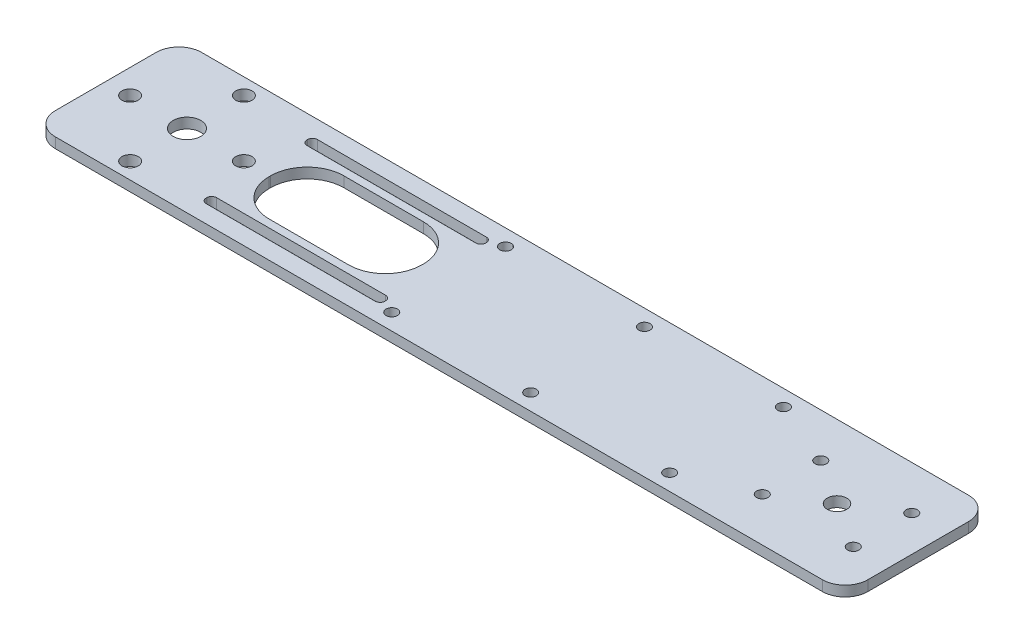
SolidWorks part; units mm, degrees
ref_plane "Front Plane" through (0, 0, 0) normal (0, 0, 1) x (1, 0, 0)
ref_plane "Top Plane" through (0, 0, 0) normal (0, 1, 0) x (1, 0, 0)
ref_plane "Right Plane" through (0, 0, 0) normal (1, 0, 0) x (0, 0, -1)
sketch "Sketch1" plane through (0, 0, 0) normal (0, 1, 0) x (1, 0, 0)
  line L0 (-25, 0) -> (0, 0) construction
  line L1 (-25, 22.5) -> (225, 22.5)
  line L2 (-25, 22.5) -> (-25, -22.5)
  line L3 (-25, -22.5) -> (225, -22.5)
  line L4 (225, 22.5) -> (225, -22.5)
  dimension "D1" = 25
  dimension "D2" = 250
  dimension "D3" = 45
extrude "Boss-Extrude1" add sketch "Sketch1" along normal blind 3.175
sketch "Sketch4" plane through (0, 3.175, 0) normal (0, 1, 0) x (1, 0, 0)
  line L0 (225, 0) -> (-25, 0) construction
  line L1 (225, -22.5) -> (225, 22.5) construction
  line L2 (-25, 22.5) -> (-25, -22.5) construction
  line L3 (200, 22.5) -> (200, -22.5) construction
  line L4 (225, 22.5) -> (-25, 22.5) construction
  line L5 (-25, -22.5) -> (225, -22.5) construction
  circle A0 centre (200, 0) radius 3
  circle A1 centre (186, 9) radius 1.75
  circle A2 centre (214, 9) radius 1.75
  circle A3 centre (214, -9) radius 1.75
  circle A4 centre (186, -9) radius 1.75
  dimension "D1" = 6
  dimension "D5" = 3.5
  dimension "D2" = 25
  dimension "D3" = 14
  dimension "D4" = 9
extrude "Cut-Extrude1" cut sketch "Sketch4" against normal through all
sketch "Sketch5" plane through (0, 3.175, 0) normal (0, 1, 0) x (1, 0, 0)
  circle A0 centre (0, 0) radius 4.25
  dimension "D1" = 8.5
extrude "Cut-Extrude2" cut sketch "Sketch5" against normal through all
sketch "Sketch6" plane through (0, 3.175, 0) normal (0, 1, 0) x (1, 0, 0)
  line L1 (45, 21) -> (45, -21) construction
  line L2 (24, 0) -> (66, 0) construction
  circle A6 centre (45, 0) radius 11.5
  circle A7 centre (29.5, 15.5) radius 1.5
  circle A8 centre (60.5, 15.5) radius 1.5
  circle A9 centre (60.5, -15.5) radius 1.5
  circle A10 centre (29.5, -15.5) radius 1.5
  point P6 (45, 0)
  point P8 (45, 0)
  dimension "D1" = 23
  dimension "D4" = 3
  dimension "D2" = 45
  dimension "D3" = 42
  dimension "D5" = 15.5
  dimension "D6" = 15.5
extrude "Cut-Extrude3" cut sketch "Sketch6" against normal through all
sketch "Sketch10" plane through (0, 3.175, 0) normal (0, 1, 0) x (1, 0, 0)
  line L0 (-25, 0) -> (225, 0) construction
  line L1 (-25, -22.5) -> (225, -22.5) construction
  line L2 (225, -22.5) -> (225, 22.5) construction
  line L3 (-25, 22.5) -> (-25, -22.5) construction
  line L4 (80.5, -17.5) -> (123.25, -17.5) construction
  line L5 (123.25, -17.5) -> (166, -17.5) construction
  circle A0 centre (80.5, -17.5) radius 1.75
  circle A1 centre (123.25, -17.5) radius 1.75
  circle A2 centre (166, -17.5) radius 1.75
  circle A3 centre (186, -9) radius 1.75 construction
  circle A4 centre (166, 17.5) radius 1.75
  circle A5 centre (80.5, 17.5) radius 1.75
  circle A6 centre (60.5, -15.5) radius 1.5 construction
  circle A7 centre (123.25, 17.5) radius 1.75
  dimension "D3" = 3.5
  dimension "D4" = 20
  dimension "D1" = 20
  dimension "D2" = 5
extrude "Cut-Extrude4" cut sketch "Sketch10" against normal through all
fillet "Fillet1" radius 7 4 edges at (-25, 1.5875, 22.5) (-25, 1.5875, -22.5) (225, 1.5875, -22.5) (225, 1.5875, 22.5)
sketch "Sketch11" plane through (0, 3.175, 0) normal (0, 1, 0) x (1, 0, 0)
  circle A0 centre (0, 17.5) radius 2.5
  circle A1 centre (17.5, 0) radius 2.5
  circle A2 centre (0, -17.5) radius 2.5
  circle A3 centre (-17.5, 0) radius 2.5
  dimension "D1" = 5
  dimension "D2" = 17.5
  dimension "D3" = 4
extrude "Cut-Extrude5" cut sketch "Sketch11" against normal through all
sketch "Sketch12" plane through (0, 3.175, 0) normal (0, 1, 0) x (1, 0, 0)
  line L0 (-25, 0) -> (225, 0) construction
  line L1 (23, 17.1) -> (75, 17.1)
  line L2 (21.5, 15.6) -> (21.5, 15.4)
  line L3 (23, 13.9) -> (75, 13.9)
  line L4 (76.5, 15.6) -> (76.5, 15.4)
  line L5 (-25, 15.5) -> (-25, -15.5) construction
  line L6 (225, -15.5) -> (225, 15.5) construction
  line L7 (76.5, -15.6) -> (76.5, -15.4)
  line L8 (23, -13.9) -> (75, -13.9)
  line L9 (21.5, -15.6) -> (21.5, -15.4)
  line L10 (23, -17.1) -> (75, -17.1)
  line L12 (36.75, 11.5) -> (61.25, 11.5)
  line L13 (25.5, 0.25) -> (25.5, -0.25)
  line L14 (36.75, -11.5) -> (61.25, -11.5)
  line L15 (72.5, 0.25) -> (72.5, -0.25)
  circle A0 centre (17.5, 0) radius 2.5 construction
  circle A1 centre (80.5, 17.5) radius 1.75 construction
  arc A3 (23, -13.9) -> (21.5, -15.4) centre (23, -15.4) ccw
  arc A4 (21.5, -15.6) -> (23, -17.1) centre (23, -15.6) ccw
  arc A5 (76.5, -15.6) -> (75, -17.1) centre (75, -15.6) cw
  arc A6 (76.5, -15.4) -> (75, -13.9) centre (75, -15.4) ccw
  arc A7 (75, 13.9) -> (76.5, 15.4) centre (75, 15.4) ccw
  arc A8 (75, 17.1) -> (76.5, 15.6) centre (75, 15.6) cw
  arc A9 (23, 17.1) -> (21.5, 15.6) centre (23, 15.6) ccw
  arc A10 (21.5, 15.4) -> (23, 13.9) centre (23, 15.4) ccw
  arc A11 (61.25, 11.5) -> (72.5, 0.25) centre (61.25, 0.25) cw
  arc A12 (61.25, -11.5) -> (72.5, -0.25) centre (61.25, -0.25) ccw
  arc A13 (25.5, -0.25) -> (36.75, -11.5) centre (36.75, -0.25) ccw
  arc A14 (36.75, 11.5) -> (25.5, 0.25) centre (36.75, 0.25) ccw
  point P4 (21.5, 15.5)
  point P24 (72.5, 0)
  point P25 (49, 11.5)
  point P26 (49, 13.9)
  point P29 (21.5, -13.9)
  point P32 (21.5, -17.1)
  point P35 (76.5, -17.1)
  point P38 (76.5, -13.9)
  point P41 (76.5, 13.9)
  point P44 (76.5, 17.1)
  point P47 (21.5, 17.1)
  point P50 (21.5, 13.9)
  point P53 (72.5, 11.5)
  point P56 (72.5, -11.5)
  dimension "D3" = 4
  dimension "D4" = 4
  dimension "D5" = 23
  dimension "D7" = 1.5
  dimension "D8" = 11.25
  dimension "D1" = 3.2
  dimension "D2" = 15.5
  dimension "D6" = 4
extrude "Cut-Extrude6" cut sketch "Sketch12" against normal through all
